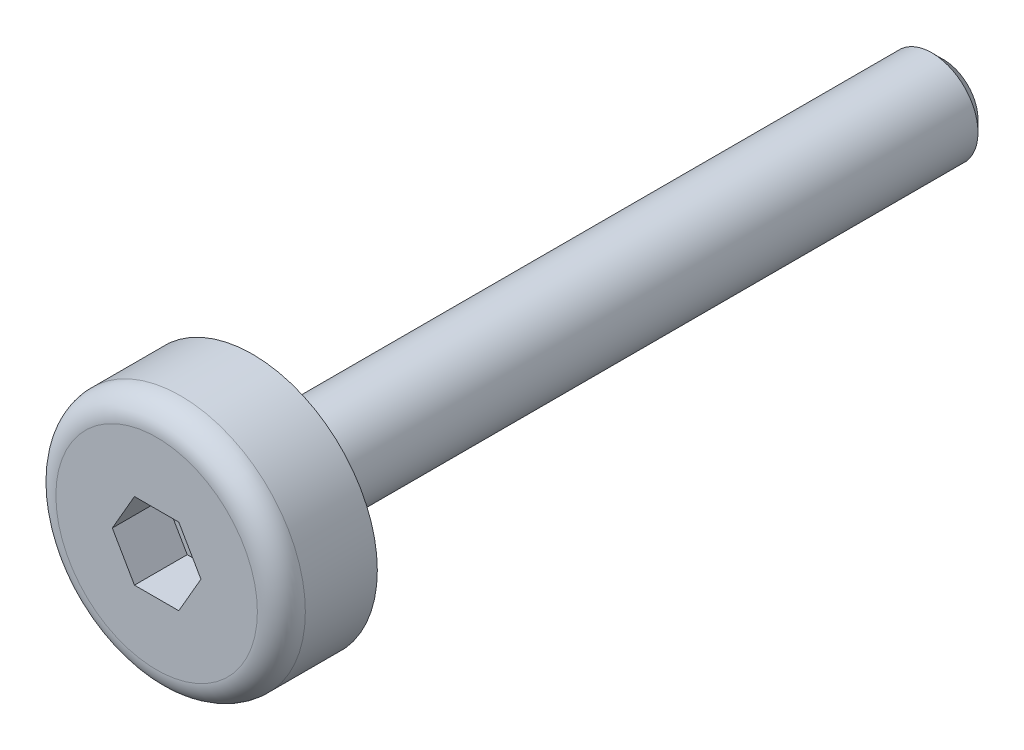
SolidWorks part; units mm, degrees
ref_plane "Front Plane" through (0, 0, 0) normal (0, 0, 1) x (1, 0, 0)
ref_plane "Top Plane" through (0, 0, 0) normal (0, 1, 0) x (1, 0, 0)
ref_plane "Right Plane" through (0, 0, 0) normal (1, 0, 0) x (0, 0, -1)
sketch "Screw Section" plane through (0, 0, 0) normal (0, 1, 0) x (1, 0, 0)
  line L0 (0, 18) -> (1.2, 18)
  line L1 (1.2, 18) -> (1.2, 0)
  line L2 (1.2, 0) -> (3.25, 0)
  line L3 (3.25, 0) -> (3.25, -2.5)
  line L4 (3.25, -2.5) -> (0, -2.5)
  line L5 (0, -2.5) -> (0, 18)
  line L6 (0, -10.123) -> (0, 10.123) construction
  dimension "D1" = 1.2
  dimension "D2" = 3.25
  dimension "D3" = 18
  dimension "D4" = 2.5
  dimension "D5" = 10.123
  dimension "D6" = 10.123
revolve "Screw Blank Revolve" add sketch "Screw Section" angle 360 about L6
chamfer "Shank Tip Chamfer" distance 0.3 1 edges at (1.2, 0, -18)
fillet "Pan Head Round" radius 0.625 1 edges at (3.25, 0, 2.5)
ref_plane "Head Crown Plane" through (0, 0, 2.5) normal (0, 0, 1) x (1, 0, 0)
sketch "Hex Drive Sketch" plane through (0, 0, 2.5) normal (0, 0, 1) x (1, 0, 0)
  line L1 (1.1547, 0) -> (0.5774, 1)
  line L2 (0.5774, 1) -> (-0.5774, 1)
  line L3 (-0.5774, 1) -> (-1.1547, 0)
  line L4 (-1.1547, 0) -> (-0.5774, -1)
  line L5 (-0.5774, -1) -> (0.5774, -1)
  line L6 (0.5774, -1) -> (1.1547, 0)
  circle A0 centre (0, 0) radius 1 construction
  dimension "D1" = 2
extrude "Hex Drive Cut" cut sketch "Hex Drive Sketch" against normal blind 1.375
equation "\"nominal_length\"= 18.0mm 'Screw length: under pan head or including flat head"
equation "\"model_shank_radius\"= 1.2mm 'Clearance envelope minor shank radius; thread is not modeled"
equation "\"head_diameter\"= 6.5mm 'Head outside diameter"
equation "\"head_height\"= 2.5mm 'Head axial height"
equation "\"drive_across_flats\"= 2mm 'Hex drive across flats"
equation "\"tip_chamfer\"= 0.3mm 'Shank tip chamfer"
equation "\"head_round\"= 0.625mm 'Pan head crown edge radius"
equation "\"drive_depth\"= 1.375mm 'Hex socket depth"
equation "\"axis_reference_halfspan\"= 10.123mm 'Half display length of the construction axis; avoids sharing a profile endpoint"
equation "\"D1@Screw Section\"= \"model_shank_radius\""
equation "\"D2@Screw Section\"= \"head_diameter\" / 2"
equation "\"D3@Screw Section\"= \"nominal_length\""
equation "\"D4@Screw Section\"= \"head_height\""
equation "\"D5@Screw Section\"= \"axis_reference_halfspan\""
equation "\"D6@Screw Section\"= \"axis_reference_halfspan\""
equation "\"full_turn\"= 360deg 'Full circular extent for revolves and patterns"
equation "\"D1@Screw Blank Revolve\"= \"full_turn\""
equation "\"D1@Shank Tip Chamfer\"= \"tip_chamfer\""
equation "\"D1@Pan Head Round\"= \"head_round\""
equation "\"D1@Head Crown Plane\"= \"head_height\""
equation "\"D1@Hex Drive Sketch\"= \"drive_across_flats\""
equation "\"D1@Hex Drive Cut\"= \"drive_depth\""
